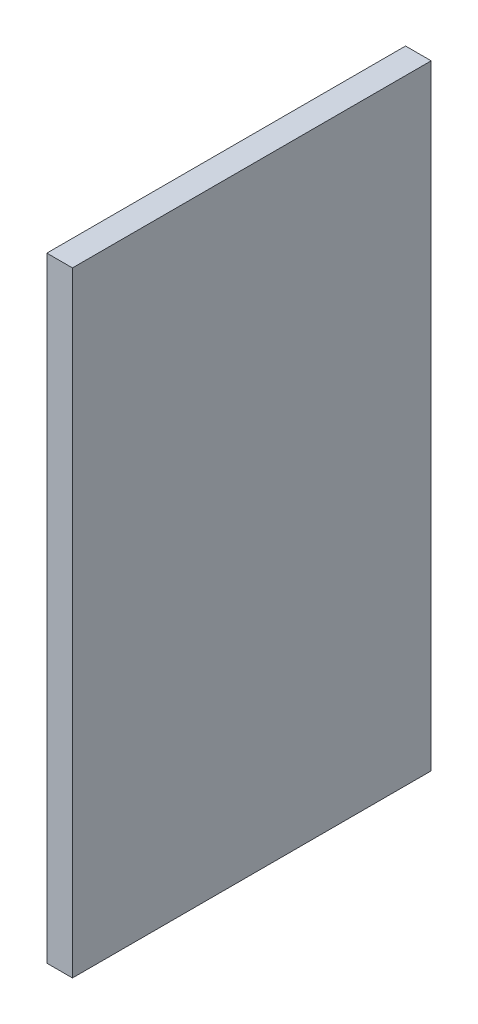
SolidWorks part; units mm, degrees
ref_plane "Alzado" through (0, 0, 0) normal (1, 0, 0) x (0, 1, 0)
ref_plane "Planta" through (0, 0, 0) normal (0, 0, 1) x (0, 1, 0)
ref_plane "Vista lateral" through (0, 0, 0) normal (0, 1, 0) x (-1, 0, 0)
sketch "Croquis2" plane through (0, 0, 0) normal (1, 0, 0) x (0, 1, 0)
  line L1 (0, 0) -> (240, 0)
  line L2 (0, 0) -> (0, 140)
  line L3 (0, 140) -> (240, 140)
  line L4 (240, 0) -> (240, 140)
  dimension "D1" = 240
  dimension "D2" = 140
extrude "Saliente-Extruir1" add sketch "Croquis2" along normal blind 10
